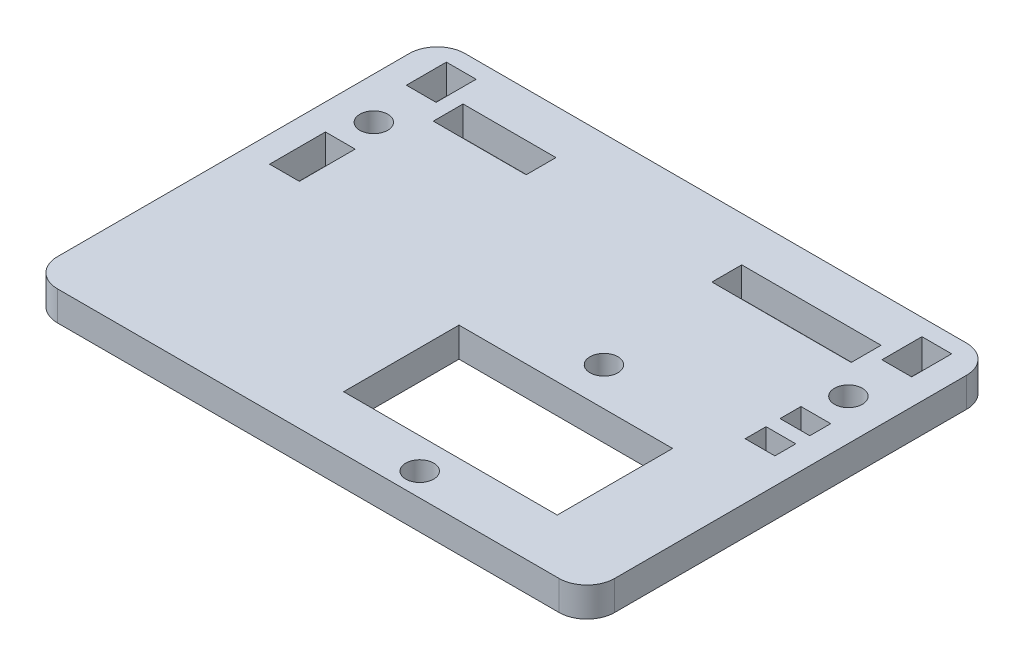
SolidWorks part; units mm, degrees
material "Acrylic (Medium-high impact)"
ref_plane "Front Plane" through (0, 0, 0) normal (0, 0, 1) x (1, 0, 0)
ref_plane "Top Plane" through (0, 0, 0) normal (0, 1, 0) x (1, 0, 0)
ref_plane "Right Plane" through (0, 0, 0) normal (1, 0, 0) x (0, 0, -1)
sketch "Sketch1" plane through (0, 0, 0) normal (0, 1, 0) x (1, 0, 0)
  line L0 (-8.8986, 14.6168) -> (-8.8988, -23.1844)
  line L1 (48.1999, -0.9368) -> (48.1999, -3.1838)
  line L2 (48.1999, -3.1838) -> (45.0054, -3.1838)
  line L3 (45.0054, -3.1838) -> (45.0054, -0.9368)
  line L4 (45.0054, -0.9368) -> (48.1999, -0.9368)
  line L5 (-6.104, 2.8166) -> (-6.104, -3.1836)
  line L6 (-6.104, -3.1836) -> (-2.9098, -3.1836)
  line L7 (-2.9098, -3.1836) -> (-2.9098, 2.8166)
  line L8 (-2.9098, 2.8166) -> (-6.104, 2.8166)
  line L9 (28.6345, 12.8168) -> (43.608, 12.8168)
  line L10 (43.608, 12.8168) -> (43.608, 9.6168)
  line L11 (43.608, 9.6168) -> (28.6345, 9.6168)
  line L12 (28.6345, 9.6168) -> (28.6345, 12.8168)
  line L13 (8.6699, 12.8168) -> (8.6699, 9.6168)
  line L14 (8.6699, 9.6168) -> (-1.3122, 9.6168)
  line L15 (-1.3122, 9.6168) -> (-1.3122, 12.8168)
  line L16 (-1.3122, 12.8168) -> (8.6699, 12.8168)
  line L17 (-5.8986, -26.1846) -> (48.0001, -26.1846)
  line L18 (50.9948, -23.1899) -> (50.9948, 14.6168)
  line L19 (47.9947, 17.6169) -> (-5.9041, 17.6169)
  line L20 (-6.1038, 11.5167) -> (-6.1038, 15.817)
  line L21 (-6.1038, 15.817) -> (-2.9096, 15.817)
  line L22 (-2.9096, 15.817) -> (-2.9096, 11.5167)
  line L23 (-2.9096, 11.5167) -> (-6.1038, 11.5167)
  line L24 (45.0054, 0.5694) -> (45.0054, 2.8164)
  line L25 (45.0054, 2.8164) -> (48.1999, 2.8164)
  line L26 (48.1999, 2.8164) -> (48.1999, 0.5694)
  line L27 (48.1999, 0.5694) -> (45.0054, 0.5694)
  line L28 (48.1999, 15.817) -> (48.1999, 11.5167)
  line L29 (48.1999, 11.5167) -> (45.0054, 11.5167)
  line L30 (45.0054, 11.5167) -> (45.0054, 15.817)
  line L31 (45.0054, 15.817) -> (48.1999, 15.817)
  line L32 (42.0107, -7.9839) -> (19.0516, -7.9839)
  line L33 (19.0516, -7.9839) -> (19.0516, -20.3844)
  line L34 (19.0516, -20.3844) -> (42.0107, -20.3844)
  line L35 (42.0107, -20.3844) -> (42.0107, -7.9839)
  arc A0 (-5.9041, 17.6169) -> (-8.8986, 14.6168) centre (-5.9041, 14.6224) ccw
  arc A1 (-8.8988, -23.1844) -> (-5.8986, -26.1846) centre (-5.8986, -23.1844) ccw
  arc A2 (48.0001, -26.1846) -> (50.9948, -23.1899) centre (48.0001, -23.1899) ccw
  arc A3 (50.9948, 14.6168) -> (47.9947, 17.6169) centre (47.9947, 14.6168) ccw
  circle A4 centre (-4.4068, 6.3166) radius 1.4999
  circle A5 centre (30.5312, -3.8842) radius 1.4999
  circle A6 centre (46.6027, 6.3164) radius 1.4999
  circle A7 centre (30.5312, -23.6847) radius 1.4999
  point P29 (-4.4068, 6.3166)
  point P32 (30.5312, -23.6847)
  point P35 (46.6027, 6.3164)
  point P42 (30.5312, -3.8842)
  dimension "D1" = 2.9999
extrude "Boss-Extrude1" add sketch "Sketch1" along normal blind 3.175
equation "\"0.025inin\"=0.045"
